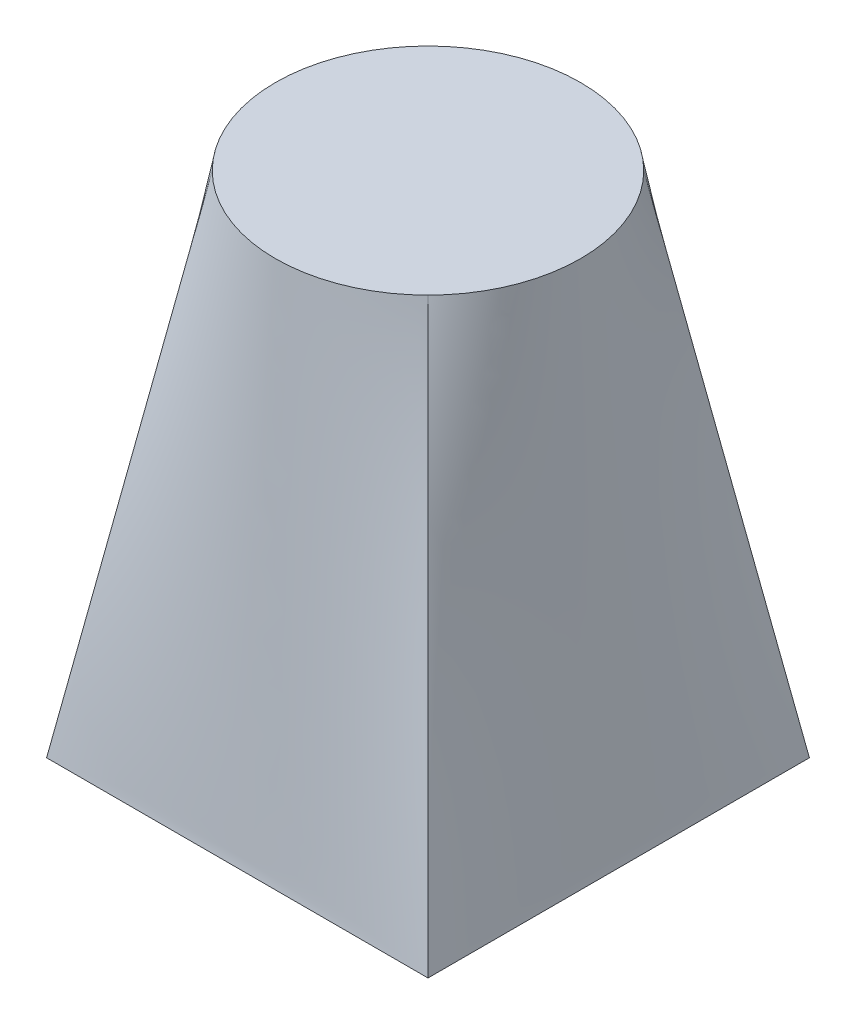
SolidWorks part; units mm, degrees
ref_plane "前视基准面" through (0, 0, 0) normal (0, 0, 1) x (1, 0, 0)
ref_plane "上视基准面" through (0, 0, 0) normal (0, 1, 0) x (1, 0, 0)
ref_plane "右视基准面" through (0, 0, 0) normal (1, 0, 0) x (0, 0, -1)
ref_plane "基准面1" through (0, 40, 0) normal (0, 1, 0) x (1, 0, 0)
sketch "草图1" plane through (0, 0, 0) normal (0, 1, 0) x (1, 0, 0)
  line L0 (-15, 15) -> (15, 15)
  line L1 (15, 15) -> (15, -15)
  line L2 (15, -15) -> (-15, -15)
  line L3 (-15, -15) -> (-15, 15)
sketch "草图2" plane through (0, 40, 0) normal (0, 1, 0) x (1, 0, 0)
  circle A0 centre (0, 0) radius 12
loft "放样1" add profiles "草图1", "草图2"
